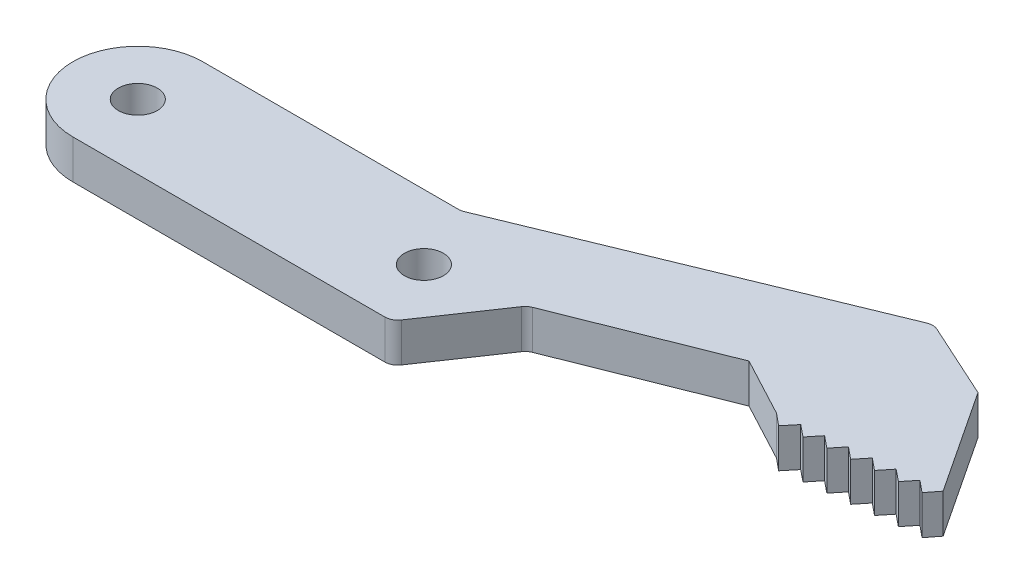
SolidWorks part; units mm, degrees
ref_plane "Front Plane" through (0, 0, 0) normal (0, 0, 1) x (1, 0, 0)
ref_plane "Top Plane" through (0, 0, 0) normal (0, 1, 0) x (1, 0, 0)
ref_plane "Right Plane" through (0, 0, 0) normal (1, 0, 0) x (0, 0, -1)
sketch "Sketch1" plane through (0, 0, 0) normal (0, 1, 0) x (1, 0, 0)
  line L1 (0, -5) -> (23.9989, -5)
  line L2 (0, 5) -> (19.6524, 5)
  line L3 (20.0327, 5.0751) -> (45.2294, 15.4347)
  line L4 (46.0242, 15.4199) -> (51.8314, 12.7746)
  line L6 (24.8266, -4.5611) -> (28.5649, 0.9541)
  line L7 (29.0223, 1.322) -> (40.9296, 6.07)
  line L11 (47.1446, 3.8294) -> (48.0617, 3.087)
  line L12 (48.0617, 3.087) -> (48.8042, 4.0041)
  line L13 (48.8042, 4.0041) -> (49.7213, 3.2617)
  line L14 (49.7213, 3.2617) -> (50.4638, 4.1788)
  line L15 (50.4638, 4.1788) -> (51.3809, 3.4364)
  line L16 (51.3809, 3.4364) -> (52.1234, 4.3535)
  line L17 (52.1234, 4.3535) -> (53.0405, 3.6111)
  line L18 (53.0405, 3.6111) -> (53.783, 4.5282)
  line L19 (53.783, 4.5282) -> (54.7001, 3.7858)
  line L20 (54.7001, 3.7858) -> (55.4426, 4.7029)
  line L30 (55.4426, 4.7029) -> (56.3445, 3.9578)
  line L33 (47.1446, 3.8294) -> (46.379, 2.8981)
  line L35 (46.379, 2.8981) -> (45.4518, 3.6602)
  line L37 (56.3445, 3.9578) -> (57.0544, 4.8687)
  line L38 (51.8314, 12.7746) -> (57.0544, 4.8687)
  line L39 (40.9296, 6.07) -> (45.4518, 3.6602)
  circle A0 centre (0, 0) radius 1.5
  arc A1 (0, 5) -> (0, -5) centre (0, 0) ccw
  circle A2 centre (22, 0) radius 1.5
  arc A3 (28.5649, 0.9541) -> (29.0223, 1.322) centre (29.3927, 0.3931) cw
  arc A6 (45.2294, 15.4347) -> (46.0242, 15.4199) centre (45.6096, 14.5098) cw
  arc A7 (19.6524, 5) -> (20.0327, 5.0751) centre (19.6524, 6) ccw
  arc A8 (23.9989, -5) -> (24.8266, -4.5611) centre (23.9989, -4) ccw
  point P27 (28.7372, 1.2083)
  point P30 (41.3048, 6.2197)
  point P33 (52.1913, 12.6106)
  point P36 (45.63, 15.5994)
  point P39 (19.85, 5)
  point P42 (24.5291, -5)
  dimension "D1" = 3
  dimension "D2" = 10
  dimension "D4" = 3
  dimension "D20" = 1
  dimension "D3" = 22
  dimension "D5" = 124.13
  dimension "D6" = 7.5
  dimension "D7" = 214.13
  dimension "D8" = 13.53
  dimension "D10" = 6.31
  dimension "D11" = 157.65
  dimension "D12" = 19.85
  dimension "D13" = 25.78
  dimension "D14" = 7.21
  dimension "D15" = 133.16
  dimension "D17" = 8.55
  dimension "D18" = 1.18
  dimension "D19" = 1.18
extrude "Boss-Extrude1" add sketch "Sketch1" along normal blind 3
